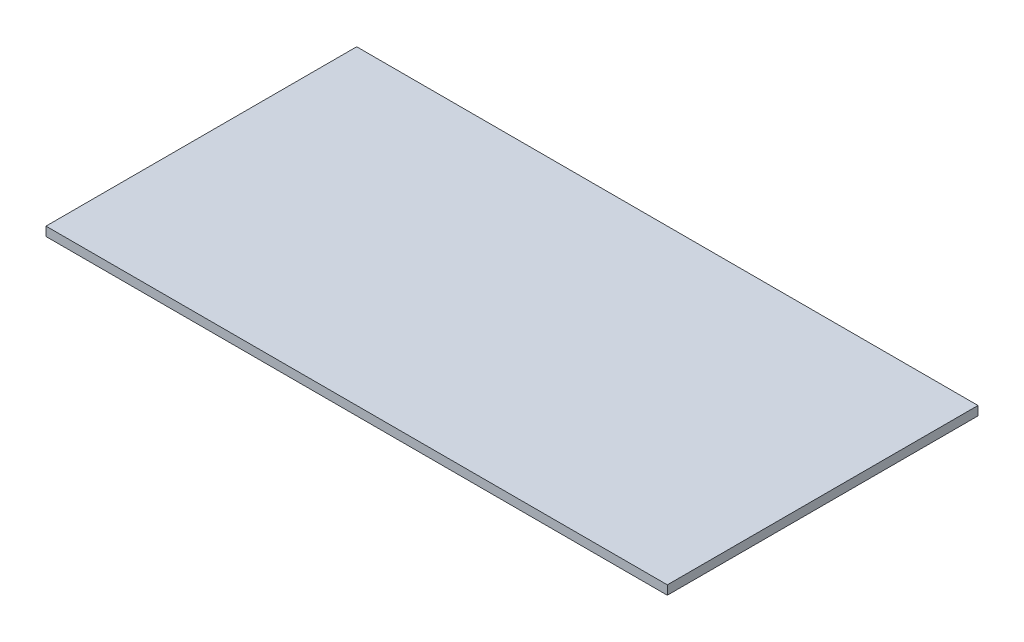
SolidWorks part; units mm, degrees
ref_plane "Front Plane" through (0, 0, 0) normal (0, 0, 1) x (1, 0, 0)
ref_plane "Top Plane" through (0, 0, 0) normal (0, 1, 0) x (1, 0, 0)
ref_plane "Right Plane" through (0, 0, 0) normal (1, 0, 0) x (0, 0, -1)
sketch "Sketch1" plane through (0, 0, 0) normal (0, 1, 0) x (1, 0, 0)
  line L1 (0, 0) -> (110, 0)
  line L2 (0, 0) -> (0, 55)
  line L3 (0, 55) -> (110, 55)
  line L4 (110, 0) -> (110, 55)
  dimension "D1" = 110
  dimension "D2" = 55
extrude "Boss-Extrude1" add sketch "Sketch1" along normal blind 1.6
